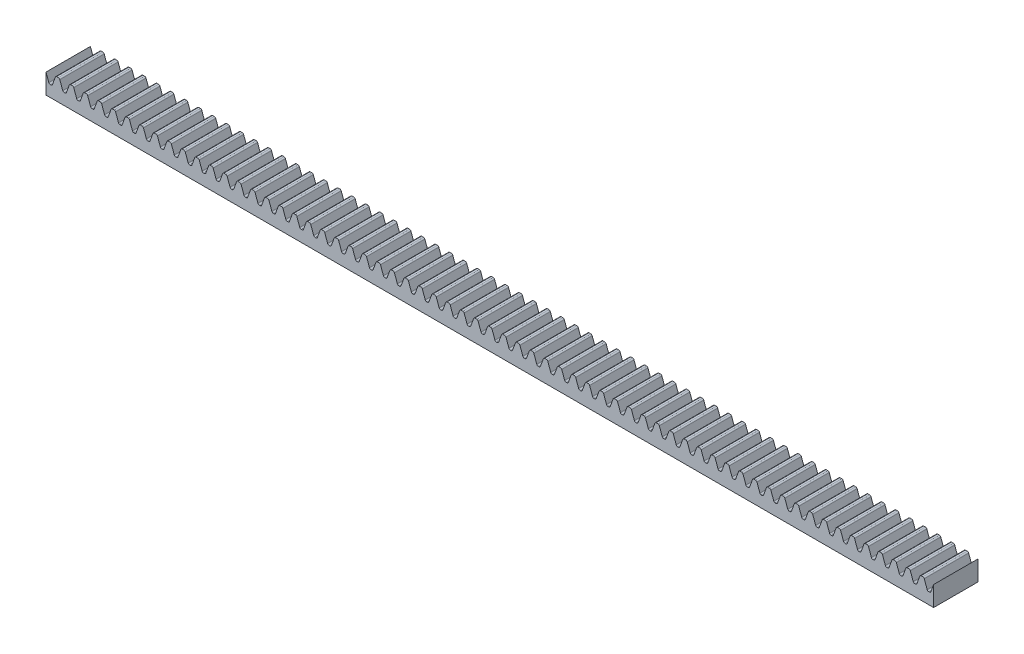
SolidWorks part; units mm, degrees
ref_plane "Front Plane" through (0, 0, 0) normal (0, 0, 1) x (1, 0, 0)
ref_plane "Top Plane" through (0, 0, 0) normal (0, 1, 0) x (1, 0, 0)
ref_plane "Right Plane" through (0, 0, 0) normal (1, 0, 0) x (0, 0, -1)
sketch "Sketch1" plane through (0, 0, 0) normal (0, 0, 1) x (1, 0, 0)
  line L0 (-50, 6) -> (-50, -6) construction
  line L1 (-50, -6) -> (50, -6) construction
  line L2 (50, -6) -> (50, 6) construction
  line L4 (0, 6) -> (0, -6) construction
  line L5 (-50, 5.5) -> (50, 5.5) construction
  line L6 (-48.9054, 6) -> (-48.484, 6) construction
  line L7 (-48.484, 6) -> (-48.0745, 4.875) construction
  line L8 (-48.9054, 6) -> (-49.3149, 4.875) construction
  line L9 (-49.3149, 4.875) -> (-48.0745, 4.875) construction
  line L10 (-48.6947, 6) -> (-48.6947, 4.875) construction
  line L11 (-50, 0) -> (-45.5531, 0) construction
  line L12 (50, 0) -> (45.5531, 0) construction
  point P15 (-47.1239, 6)
  point P16 (-31.5, -6)
  point P17 (-48.302, 5.5)
  point P18 (-49.0874, 5.5)
  point P21 (-0.25, -6)
  dimension "Length" = 100
  dimension "Height" = 12
  dimension "Approximate Number of Teeth" = 63
  dimension "Pressure Angle" = 20
  dimension "Circular Pitch" = 1.5708
  dimension "Addendum" = 0.5
  dimension "Dedendum" = 0.625
  dimension "Circular Tooth Thickness" = 0.7854
  dimension "Module" = 0.5
  dimension "Rack Length" = 97.3894
  dimension "D1" = 3.1416
sketch "Sketch2" plane through (0, 0, 0) normal (1, 0, 0) x (0, 0, -1)
  line L0 (-2.5, 0) -> (2.5, 0) construction
  dimension "Face Width" = 5
sketch "Sketch3" plane through (0, 0, 0) normal (0, 0, 1) x (1, 0, 0)
  line L1 (-50, 6) -> (50, 6)
  line L2 (-50, 6) -> (-50, -6)
  line L3 (-50, -6) -> (50, -6)
  line L4 (50, 6) -> (50, -6)
extrude "Boss-Extrude1" add sketch "Sketch3" against normal up to vertex (2.5 mm away) and the other way up to vertex (2.5 mm away) up to point (0, 0, -2.5) other way up to point (0, 0, 2.5)
sketch "Sketch4" plane through (0, 0, 0) normal (0, 0, 1) x (1, 0, 0)
  line L0 (-48.6947, 6) -> (-47.1239, 6) construction
  line L9 (-47.9093, 6) -> (-47.9093, 4.875)
  line L10 (-47.9093, 4.875) -> (-48.0745, 4.875)
  line L11 (-48.0745, 4.875) -> (-48.484, 6)
  line L12 (-48.484, 6) -> (-47.9093, 6)
  line L13 (-48.9054, 6) -> (-49.3149, 4.875)
  line L14 (-49.3149, 4.875) -> (-49.4801, 4.875)
  line L15 (-49.4801, 4.875) -> (-49.4801, 6)
  line L16 (-49.4801, 6) -> (-48.9054, 6)
  line L17 (50, 6) -> (-50, 6) construction
  line L18 (-48.9054, 6) -> (-48.7879, 6)
  line L19 (-48.6014, 6) -> (-48.484, 6)
  arc A0 (-49.4323, 4.875) -> (-49.2747, 4.9854) centre (-49.4323, 5.0428) ccw
  arc A1 (-48.1147, 4.9854) -> (-47.957, 4.875) centre (-47.957, 5.0428) ccw
  arc A2 (-48.9456, 5.8896) -> (-48.7879, 6) centre (-48.7879, 5.8322) cw
  arc A3 (-48.6014, 6) -> (-48.4438, 5.8896) centre (-48.6014, 5.8322) cw
  dimension "D1" = 0.1678
extrude "Cut-Extrude1" cut sketch "Sketch4" against normal through all both and the other way through all contours L14 A0 L13 L16 L15 | L13 A2 L18 | L19 A3 L11 | L11 A1 L10 L9 L12
pattern_linear "LPattern1" count 64 spacing 1.5708 along (1, 0, 0) count 2 spacing 1.5708 along (-1, 0, 0) of "Cut-Extrude1"
sketch "Drawing Refernce 1" plane through (0, 0, 2.5) normal (0, 0, 1) x (1, 0, 0)
  line L0 (-50, 0) -> (50, 0) construction
  point P6 (-35, 0)
  point P7 (-27.5, 0)
  point P8 (35, 0)
  dimension "D1" = 15
  dimension "D2" = 22.5
  dimension "D3" = 15
sketch "Sketch5" plane through (0, 0, 2.5) normal (0, 0, 1) x (1, 0, 0)
  line L0 (50, -6) -> (50, 5.8495) construction
  line L1 (-50, -6) -> (50, -6)
  line L2 (-50, -6) -> (-50, -1.9)
  line L3 (-50, -1.9) -> (50, -1.9)
  line L4 (50, -6) -> (50, -1.9)
  dimension "D1" = 4.1
extrude "Cut-Extrude2" cut sketch "Sketch5" against normal through all
sketch "Sketch6" plane through (0, 0, 2.5) normal (0, 0, 1) x (1, 0, 0)
  line L0 (50, -1.9) -> (50, 5.8495) construction
  line L1 (-50, -1.9) -> (50, -1.9)
  line L2 (-50, -1.9) -> (-50, 3.6)
  line L3 (-50, 3.6) -> (50, 3.6)
  line L4 (50, -1.9) -> (50, 3.6)
  dimension "D1" = 5.5
extrude "Cut-Extrude3" cut sketch "Sketch6" against normal through all
equation "\"Diametral Pitch\"= 1 / \"Module\""
equation "\"Pressure Angle\"=20"
equation "\"Dedendum\"= 1.25 / \"Diametral Pitch\""
equation "\"Addendum\"= 1 / \"Diametral Pitch\""
equation "\"WorkingDepth\"= 2 / \"Diametral Pitch\""
equation "\"WholeDepth\"= 2.25 / \"Diametral Pitch\""
equation "\"Clearance\"= 0.25 / \"Diametral Pitch\""
equation "\"ToothThickness\"= ( pi / 2 ) / \"Diametral Pitch\""
equation "\"CircularPitch\"= pi / \"Diametral Pitch\""
equation "\"Fillet\"= \"Clearance\" * cos ( \"Pressure Angle\" ) * tan ( ( 90 + \"Pressure Angle\" ) / 2 )"
equation "\"Module\"= 0.5"
equation "\"Addendum@Sketch1\"=\"Addendum\""
equation "\"Pressure Angle@Sketch1\"=\"Pressure Angle\""
equation "\"Dedendum@Sketch1\"=\"Dedendum\""
equation "\"Circular Pitch@Sketch1\"=\"CircularPitch\""
equation "\"Circular Tooth Thickness@Sketch1\"=\"ToothThickness\""
equation "\"Module@Sketch1\"=\"Module\""
equation "\"Approximate Number of Teeth@Sketch1\" = int ( \"Length@Sketch1\" /  ( 2 * \"Circular Tooth Thickness@Sketch1\" )  ) "
equation "\"Rack Length@Sketch1\" = \"Circular Pitch@Sketch1\" *  ( \"Approximate Number of Teeth@Sketch1\" - 1 ) "
equation "\"D3@LPattern1\"=\"CircularPitch\""
equation "\"D1@LPattern1\"=\"Approximate Number of Teeth@Sketch1\"+1"
equation "\"D1@Sketch1\"=\"Circular Pitch@Sketch1\"*2"
equation "\"D1@Sketch4\"=\"Fillet\""
equation "\"D4@LPattern1\"=\"CircularPitch\""
equation "\"D2@Drawing Refernce 1\"=\"D1@Drawing Refernce 1\"*1.5"
equation "\"D3@Drawing Refernce 1\"=\"D1@Drawing Refernce 1\""
